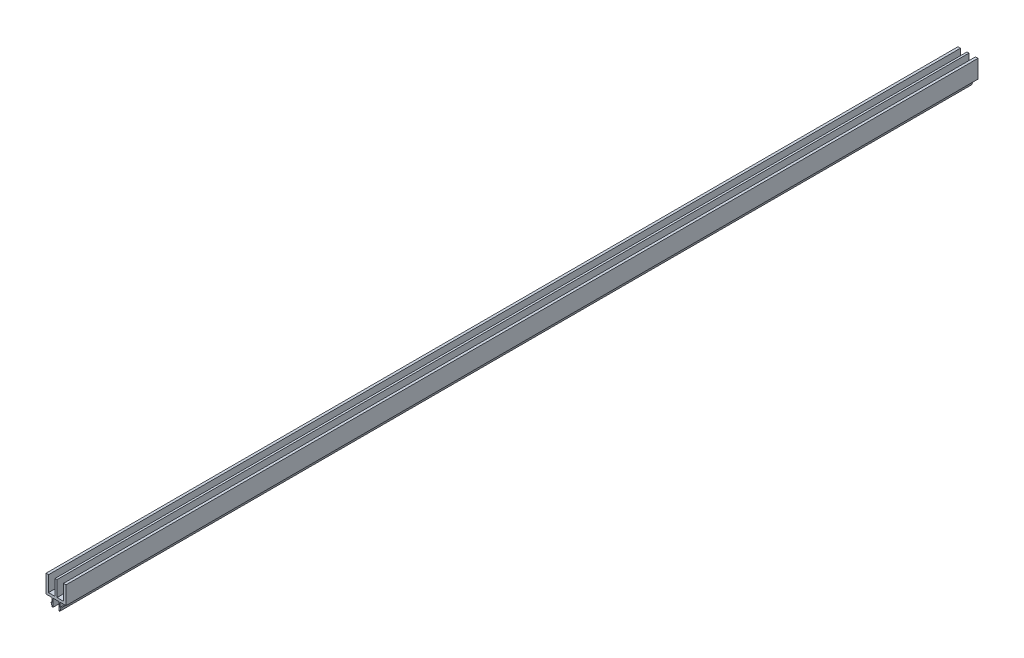
SolidWorks part; units mm, degrees
ref_plane "Plan de face" through (0, 0, 0) normal (0, 0, 1) x (1, 0, 0)
ref_plane "Plan de dessus" through (0, 0, 0) normal (0, 1, 0) x (1, 0, 0)
ref_plane "Plan de droite" through (0, 0, 0) normal (1, 0, 0) x (0, 0, -1)
ref_plane "Plan1" through (0, 0, 50) normal (0, 0, 1) x (1, 0, 0)
sketch "Esquisse1" plane through (0, 0, 50) normal (0, 0, 1) x (1, 0, 0)
  line L0 (-1, 2.5) -> (-7.5, 2.5)
  line L1 (-7.5, 2.5) -> (-7.5, 18)
  line L2 (-7.5, 18) -> (-10, 18)
  line L3 (-10, 18) -> (-10, 0)
  line L4 (-10, 0) -> (-4, 0)
  line L5 (-4, 0) -> (-4, -4.5)
  line L6 (-4, -4.5) -> (-5, -4.5)
  line L7 (-5, -4.5) -> (-3.75, -8)
  line L8 (-3.75, -8) -> (-3, -8)
  line L9 (-3, -8) -> (-3, 0)
  line L10 (-3, 0) -> (3, 0)
  line L11 (3, 0) -> (3, -8)
  line L12 (3, -8) -> (3.75, -8)
  line L13 (3.75, -8) -> (5, -4.5)
  line L14 (5, -4.5) -> (4, -4.5)
  line L15 (4, -4.5) -> (4, 0)
  line L16 (4, 0) -> (10, 0)
  line L17 (10, 0) -> (10, 18)
  line L18 (10, 18) -> (7.5, 18)
  line L19 (7.5, 18) -> (7.5, 2.5)
  line L20 (7.5, 2.5) -> (1, 2.5)
  line L21 (1, 2.5) -> (1, 18)
  line L22 (1, 18) -> (-1, 18)
  line L23 (-1, 18) -> (-1, 2.5)
extrude "Boss.-Extru.1" add sketch "Esquisse1" against normal blind 910
